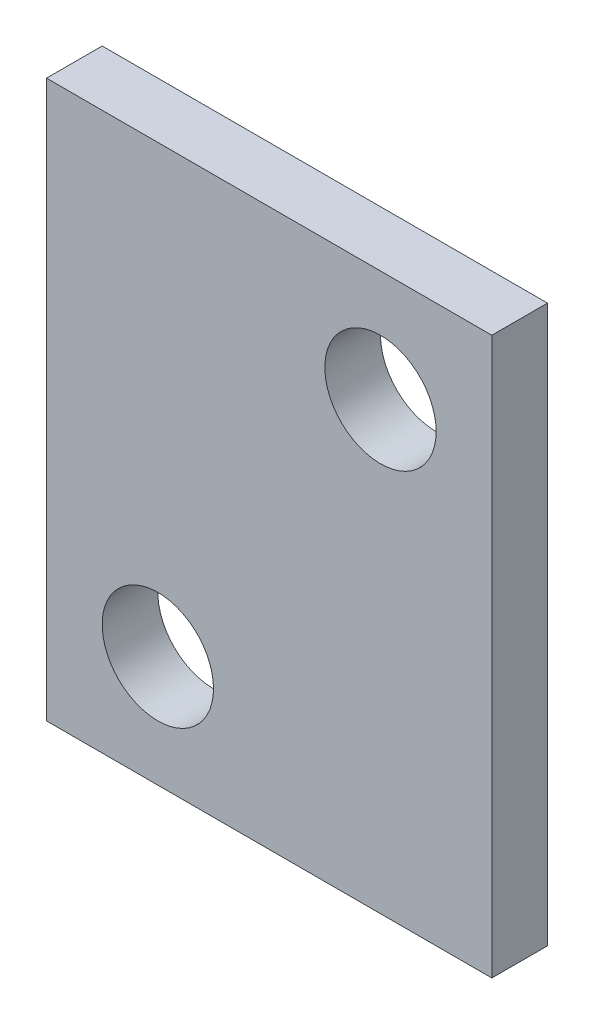
SolidWorks part; units mm, degrees
ref_plane "Plan de face" through (0, 0, 0) normal (0, 0, 1) x (1, 0, 0)
ref_plane "Plan de dessus" through (0, 0, 0) normal (0, 1, 0) x (1, 0, 0)
ref_plane "Plan de droite" through (0, 0, 0) normal (1, 0, 0) x (0, 0, -1)
sketch "Esquisse1" plane through (0, 0, 0) normal (0, 0, 1) x (1, 0, 0)
  line L1 (-15.5206, 10.2965) -> (-3.5206, 10.2965)
  line L2 (-15.5206, 10.2965) -> (-15.5206, -4.7035)
  line L3 (-15.5206, -4.7035) -> (-3.5206, -4.7035)
  line L4 (-3.5206, 10.2965) -> (-3.5206, -4.7035)
  circle A0 centre (-6.5206, 7.2965) radius 1.5
  circle A1 centre (-12.5206, -1.7035) radius 1.5
  dimension "D3" = 3
  dimension "D1" = 15
  dimension "D2" = 12
  dimension "D4" = 3
  dimension "D5" = 3
  dimension "D6" = 3
extrude "Extrusion1" add sketch "Esquisse1" along normal blind 1.5
